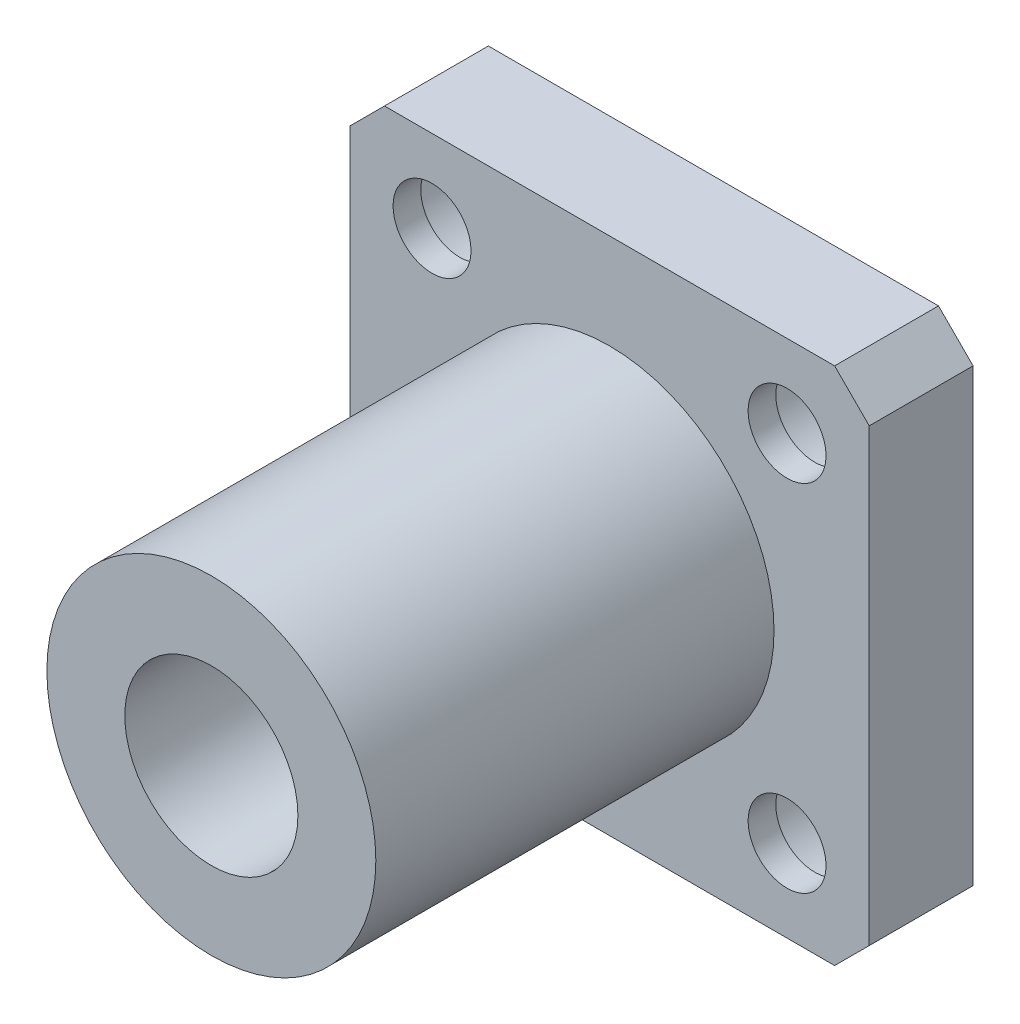
SolidWorks part; units mm, degrees
ref_plane "Płaszczyzna przednia" through (0, 0, 0) normal (0, 0, 1) x (1, 0, 0)
ref_plane "Płaszczyzna górna" through (0, 0, 0) normal (0, 1, 0) x (1, 0, 0)
ref_plane "Płaszczyzna prawa" through (0, 0, 0) normal (1, 0, 0) x (0, 0, -1)
sketch "Sketch1" plane through (0, 0, 0) normal (0, 0, 1) x (1, 0, 0)
  line L1 (0, 0) -> (30, 0)
  line L2 (0, 0) -> (0, 30)
  line L3 (0, 30) -> (30, 30)
  line L4 (30, 0) -> (30, 30)
  dimension "K" = 30
extrude "Boss-Extrude1" add sketch "Sketch1" along normal blind 6
sketch "Sketch2" plane through (0, 0, 6) normal (0, 0, 1) x (1, 0, 0)
  line L0 (0, 15) -> (30, 15) construction
  line L1 (0, 30) -> (0, 0) construction
  line L2 (30, 0) -> (30, 30) construction
  line L3 (15, 0) -> (15, 30) construction
  line L4 (0, 0) -> (30, 0) construction
  line L5 (30, 30) -> (0, 30) construction
  circle A0 centre (15, 15) radius 9.5
  point P14 (0, 0)
  point P15 (15, 15)
  dimension "D" = 19
extrude "Boss-Extrude2" add sketch "Sketch2" along normal blind 23
sketch "Sketch3" plane through (0, 0, 29) normal (0, 0, 1) x (1, 0, 0)
  circle A0 centre (15, 15) radius 5
  dimension "D1" = 10
extrude "Cut-Extrude1" cut sketch "Sketch3" against normal through all
sketch "Sketch4" plane through (0, 0, 0) normal (0, 0, -1) x (-1, 0, 0)
  circle A0 centre (-15, 15) radius 14.5 construction
  dimension "PCD" = 29
hole_wizard "CBORE for M5 Hex Head Bolt1" positions "Sketch8" profile "Sketch6" counterbore size "M5" standard "ANSI Metric" end condition through all
sketch "Sketch8" plane through (0, 0, 0) normal (0, 0, -1) x (-1, 0, 0)
  line L0 (-29.5, 15) -> (-15, 29.5) construction
  line L2 (-22.25, 22.25) -> (-30, 30) construction
  circle A0 centre (-15, 15) radius 14.5 construction
  point P0 (-25.253, 25.253)
  point P22 (-4.747, 25.253)
  point P23 (-4.747, 4.747)
  point P24 (-25.253, 4.747)
  dimension "D1" = 4
sketch "Sketch6" plane through (25.253, 25.253, 0) normal (1, 0, 0) x (0, 1, 0)
  line L0 (0, 0) -> (0, 29)
  line L1 (0, 29) -> (2.25, 29)
  line L3 (2.25, 29) -> (2.25, 4.4)
  line L4 (2.25, 4.4) -> (4, 4.4)
  line L5 (4, 4.4) -> (4, 0)
  line L7 (4, 0) -> (0, 0)
  line L11 (0, -6.35) -> (0, 107.95) construction
  dimension "Thru Hole Dia." = 4.5
  dimension "Thru Hole Depth" = 29
  dimension "C'Bore Dia." = 8
  dimension "C'Bore Depth" = 4.4
chamfer "Chamfer1" distance 2 angle 45 4 edges at (0, 30, 3) (30, 30, 3) (30, 0, 3) (0, 0, 3)
